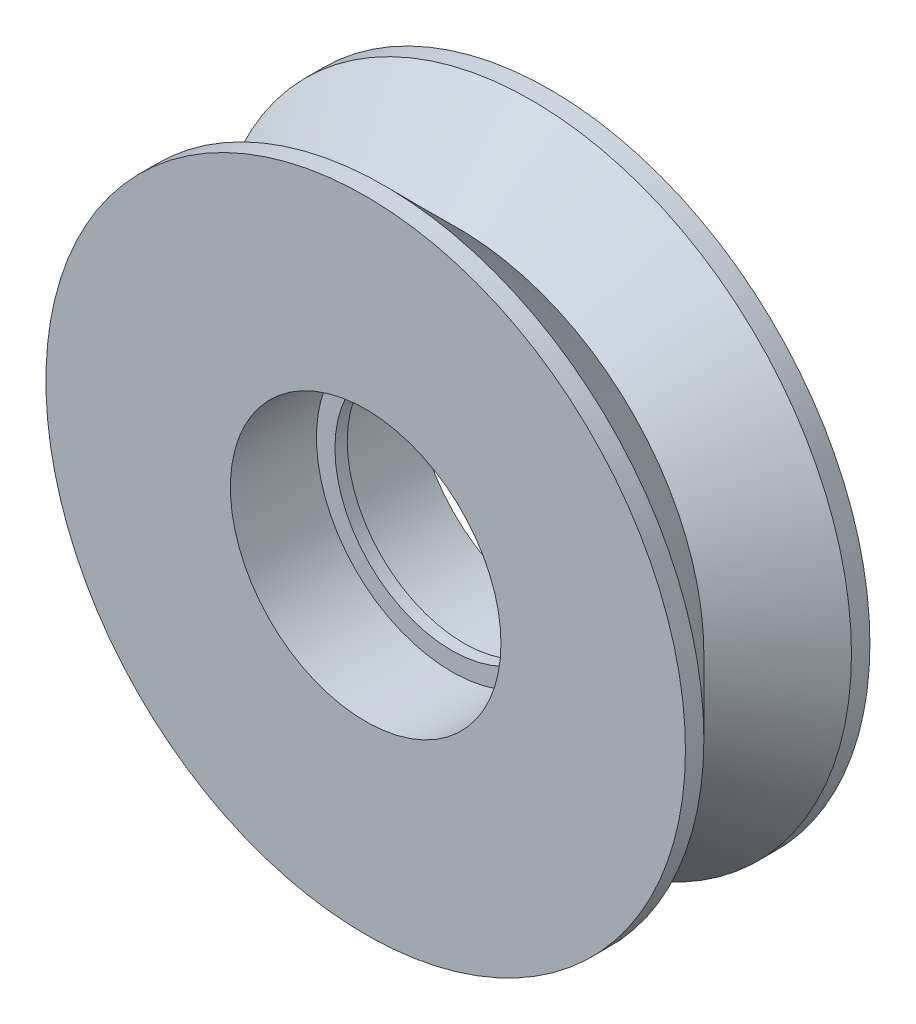
SolidWorks part; units mm, degrees
ref_plane "前视基准面" through (0, 0, 0) normal (0, 0, 1) x (1, 0, 0)
ref_plane "上视基准面" through (0, 0, 0) normal (0, 1, 0) x (1, 0, 0)
ref_plane "右视基准面" through (0, 0, 0) normal (1, 0, 0) x (0, 0, -1)
other "Configuration Table"
sketch "草图1" plane through (0, 0, 0) normal (0, 1, 0) x (1, 0, 0)
  line L0 (11, 0) -> (26, 0)
  line L1 (26, 0) -> (26, 1.5)
  line L2 (26, 1.5) -> (20, 7.5)
  line L3 (20, 7.5) -> (26, 13.5)
  line L4 (26, 13.5) -> (26, 15)
  line L5 (26, 15) -> (11, 15)
  line L6 (11, 15) -> (11, 8)
  line L7 (11, 8) -> (9.5, 8)
  line L8 (9.5, 8) -> (9.5, 7)
  line L9 (9.5, 7) -> (11, 7)
  line L10 (11, 7) -> (11, 0)
  line L11 (0, -5) -> (0, 5) construction
revolve "旋转1" add sketch "草图1" angle 360 about L11
